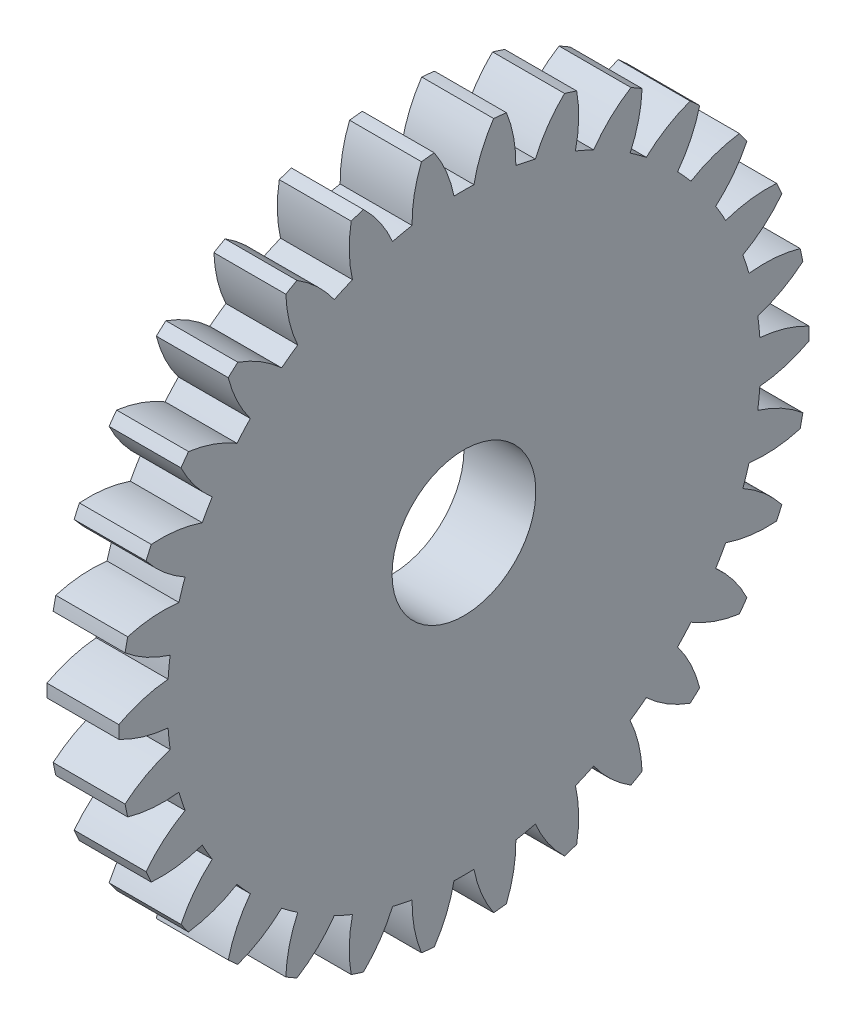
SolidWorks part; units mm, degrees
ref_plane "Plane1" through (0, 0, 0) normal (0, 0, 1) x (1, 0, 0)
ref_plane "Plane2" through (0, 0, 0) normal (0, 1, 0) x (1, 0, 0)
ref_plane "Plane3" through (0, 0, 0) normal (1, 0, 0) x (0, 0, -1)
sketch "HoldingSke" plane through (0, 0, 0) normal (0, 1, 0) x (1, 0, 0)
  line L0 (0, 0) -> (0.5774, -0.3333)
  line L1 (-15, 0) -> (100, 0) construction
  line L2 (0, 0) -> (-2.1039, 2.3779)
  line L3 (0, 0) -> (-11.863, 4.5341)
  line L4 (0, 0) -> (7.479, 4.318)
  line L5 (0, 0) -> (-46.8476, -17.4728)
  line L6 (0, 0) -> (-4.1448, -2.7965)
  line L7 (-2.1039, 2.3779) -> (8.6586, 51.2059)
  line L8 (-76.2, 54.61) -> (-74.4, 54.61)
  line L9 (-71.009, 38.7566) -> (-53.1078, 45.2721)
  line L10 (-76.2, 71.12) -> (104.1128, 71.12)
  line L11 (0, 0) -> (-5, 0)
  line L12 (-76.2, 101.6) -> (-76.147, 101.6)
  line L13 (24.9733, 27.94) -> (52.9518, 28.4284)
  line L14 (24.9733, 27.94) -> (24.9743, 27.94)
  line L15 (24.9733, 27.94) -> (100.4006, 29.5858)
  line L16 (-63.627, -1.5) -> (-12.827, -1.5)
  circle A0 centre (0, 0) radius 5
  circle A1 centre (0, 0) radius 20.624
  circle A2 centre (0, 0) radius 37.5
  circle A3 centre (0, 0) radius 5
  dimension "MHD" = 41.248
  dimension "Hub_dia" = 75
  dimension "Bore" = 10
  dimension "MBD" = 10
  dimension "Num_teeth" = 30
  dimension "Pitch" = 0.6667
  dimension "Overall_len" = 50
  dimension "Show_teeth" = 30
  dimension "OAL" = 50.0001
  dimension "T_dim" = 1.8
  dimension "Ap" = 20
  dimension "H" = 19.05
  dimension "Pitch_radius" = 180.3128
  dimension "Backlash" = 0.053
  dimension "Addendum_fac" = 1
  dimension "Dedendum_fac" = 1.25
  dimension "Clearance_fac" = 0.25
  dimension "Dedendum_add" = 0.001
  dimension "Module" = 1.5
sketch "BasProSke" plane through (0, 0, 0) normal (0, 1, 0) x (1, 0, 0)
  line L0 (-10, 0) -> (60, 0) construction
  line L1 (0, 0) -> (0, 24)
  line L2 (0, 0) -> (5, 0)
  line L3 (5, 0) -> (5, 24)
  line L4 (5, 24) -> (0, 24)
  dimension "Diameter" = 48
revolve "Base-Revolve" add sketch "BasProSke" angle 360 about L0
sketch "TooCutSke" plane through (0, 0, 0) normal (1, 0, 0) x (0, 0, -1)
  line L1 (0, 0) -> (0, 107) construction
  line L2 (0, 0) -> (-1.2703, 22.4641) construction
  line L3 (0, 0) -> (-4.6983, 44.7014) construction
  line L4 (-1.2703, 22.4641) -> (-2.3492, 22.3507) construction
  arc A0 (0.6933, 20.6123) -> (-0.6933, 20.6123) centre (0, 0) ccw
  arc A1 (2.0805, 23.9351) -> (-2.0805, 23.9351) centre (0, 0) ccw
  circle A2 centre (0, 0) radius 22.5 construction
  circle A3 centre (0, 0) radius 21.1431 construction
  arc A4 (-0.6933, 20.6123) -> (-2.0805, 23.9351) centre (-9.5243, 18.8764) ccw
  arc A5 (2.0805, 23.9351) -> (0.6933, 20.6123) centre (9.5243, 18.8764) ccw
  dimension "Root_dia" = 41.248
  dimension "Overcut_dia" = 48.0508
  dimension "Pitch_dia" = 45
  dimension "Base_dia" = 42.2862
  dimension "Flank_rad" = 9
  dimension "Half_ang" = 6
  dimension "Half_CT" = 1.0848
extrude "ToothCut" cut sketch "TooCutSke" along normal through all
fillet "Breaks" [suppressed] radius 0.03
fillet "RootFillets" [suppressed] radius 0.376
pattern_circular "TeethCuts" count 30 every 12 about axis through (-10, 0, 0) along (1, 0, 0) of "ToothCut", "RootFillets", "Breaks"
sketch "HubNeaOneSke" plane through (0, 0, 0) normal (-1, 0, 0) x (0, 0, 1)
  circle A0 centre (0, 0) radius 20.624
  dimension "Diameter" = 41.248
extrude "HubNearOne" [suppressed] add sketch "HubNeaOneSke" along normal blind 45.0001
sketch "HubNeaBotSke" plane through (0, 0, 0) normal (-1, 0, 0) x (0, 0, 1)
  circle A0 centre (0, 0) radius 20.624
  dimension "Diameter" = 41.248
extrude "HubNearBoth" [suppressed] add sketch "HubNeaBotSke" along normal blind 22.5
ref_plane "FarPln" through (5, 0, 0) normal (1, 0, 0) x (0, 0, -1)
sketch "HubFarSke" plane through (5, 0, 0) normal (1, 0, 0) x (0, 0, -1)
  circle A0 centre (0, 0) radius 20.624
  dimension "Diameter" = 41.248
extrude "HubFar" [suppressed] add sketch "HubFarSke" along normal blind 22.5
sketch "BorSke" plane through (0, 0, 0) normal (1, 0, 0) x (0, 0, -1)
  circle A0 centre (0, 0) radius 5
  dimension "Diameter" = 10
extrude "Bore" cut sketch "BorSke" along normal mid plane 100.0001
sketch "KeySke" plane through (0, 0, 0) normal (1, 0, 0) x (0, 0, -1)
  line L0 (-2, 0) -> (-2, 6.8)
  line L1 (-2, 6.8) -> (2, 6.8)
  line L2 (2, 6.8) -> (2, 0)
  line L3 (0, 0) -> (0, 34) construction
  line L4 (-2, 0) -> (2, 0)
  dimension "Offset" = 6.8
  dimension "Width" = 4
extrude "Keyway" [suppressed] cut sketch "KeySke" along normal mid plane 100.0001
pattern_circular "Keyway2" [suppressed] count 2 every 90 about axis through (-10, 0, 0) along (1, 0, 0)
equation "' \"Module@HoldingSke\" = 6.35"
equation "' \"Num_teeth@HoldingSke\" = 12"
equation "' \"Ap@HoldingSke\" =  20"
equation "' \"Ap@HoldingSke\" = 20"
equation "' \"Width@HoldingSke\" = 0.5 * 25.4"
equation "' \"Hub_dia@HoldingSke\"= 1 * 25.4"
equation "' \"Hub_dia@HoldingSke\" = 1 * 25.4"
equation "' \"Overall_len@HoldingSke\" = 1.0 * 25.4"
equation "' \"Bore@HoldingSke\" = 0.75 * 25.4"
equation "' \"T_dim@HoldingSke\" = 0.1 * 25.4"
equation "' \"Width@KeySke\" = 0.25 * 25.4"
equation "' \"Show_teeth@HoldingSke\" = 13"
equation "' \"Backlash@HoldingSke\" = 0.009 * 25.4"
equation "' \"Addendum_fac@HoldingSke\" = 1.0"
equation "' \"Dedendum_fac@HoldingSke\" = 1.25"
equation "' \"Dedendum_add@HoldingSke\" = 0.00005 * 25.4"
equation "' \"Clearance_fac@HoldingSke\" = 0.25"
equation "\"Pitch@HoldingSke\" = 1 / \"Module@HoldingSke\""
equation "\"Overcut_dia@TooCutSke\" = (\"Num_teeth@HoldingSke\" + 2 * \"Addendum_fac@HoldingSke\") / \"Pitch@HoldingSke\" + 0.002 * 25.4"
equation "\"Pitch_dia@TooCutSke\" = \"Num_teeth@HoldingSke\" / \"Pitch@HoldingSke\""
equation "\"Base_dia@TooCutSke\" = \"Num_teeth@HoldingSke\" / \"Pitch@HoldingSke\" * cos((\"Ap@HoldingSke\"  * 3.14159265 / 180))"
equation "\"Root_dia@TooCutSke\" = (\"Num_teeth@HoldingSke\" + 2) / \"Pitch@HoldingSke\" - 2 * (\"Addendum_fac@HoldingSke\" + \"Dedendum_fac@HoldingSke\") / \"Pitch@HoldingSke\" - \"Dedendum_add@HoldingSke\" * 2"
equation "\"Half_ang@TooCutSke\" = 180 / \"Num_teeth@HoldingSke\""
equation "\"Half_CT@TooCutSke\" = \"Num_teeth@HoldingSke\" / \"Pitch@HoldingSke\" * sin((3.14159265 / 2 / \"Num_teeth@HoldingSke\")) / 2 - 7 * \"Backlash@HoldingSke\" / 4"
equation "\"Flank_rad@TooCutSke\" = \"Num_teeth@HoldingSke\" / \"Pitch@HoldingSke\" / 5"
equation "\"Radius@RootFillets\" = \"Clearance_fac@HoldingSke\" / \"Pitch@HoldingSke\" + \"Dedendum_add@HoldingSke\""
equation "\"Break_rad@Breaks\" = 0.02 / \"Pitch@HoldingSke\""
equation "\"Thickness@HoldingSke\" = \"Width@HoldingSke\""
equation "\"OAL@HoldingSke\" = \"Thickness@HoldingSke\""
equation "\"MHD@HoldingSke\" = (\"Num_teeth@HoldingSke\" + 2) / \"Pitch@HoldingSke\" - 2 * (\"Addendum_fac@HoldingSke\" + \"Dedendum_fac@HoldingSke\")  / \"Pitch@HoldingSke\" - \"Dedendum_add@HoldingSke\" * 2"
equation "\"MBD@HoldingSke\" = (\"Num_teeth@HoldingSke\" + 2) / \"Pitch@HoldingSke\" - 2 * (\"Addendum_fac@HoldingSke\" + \"Dedendum_fac@HoldingSke\")  / \"Pitch@HoldingSke\" - \"Dedendum_add@HoldingSke\" * 2 - 0.002 * 25.4"
equation "\"MHD@HoldingSke\" = ((sgn( \"MHD@HoldingSke\" - \"Hub_dia@HoldingSke\" )-1)*( \"MHD@HoldingSke\" - \"Hub_dia@HoldingSke\" ))/-2+ \"Hub_dia@HoldingSke\""
equation "\"MBD@HoldingSke\" = ((sgn( \"MBD@HoldingSke\" - \"Bore@HoldingSke\" )-1)*( \"MBD@HoldingSke\" - \"Bore@HoldingSke\" ))/-2+ \"Bore@HoldingSke\""
equation "\"OAL@HoldingSke\" = ((sgn( \"OAL@HoldingSke\" - \"Overall_len@HoldingSke\" )+1)*( \"OAL@HoldingSke\" - \"Overall_len@HoldingSke\" ))/2 + \"Overall_len@HoldingSke\" + 0.000002 * 25.4"
equation "\"Num_teeth@TeethCuts\" = int( \"Show_teeth@HoldingSke\" ) + 1"
equation "\"Num_teeth@TeethCuts\" = ((sgn( \"Num_teeth@TeethCuts\" - \"Num_teeth@HoldingSke\" )-1)*( \"Num_teeth@TeethCuts\" - \"Num_teeth@HoldingSke\" ))/-2+ \"Num_teeth@HoldingSke\""
equation "\"Num_teeth@TeethCuts\" = ((sgn( \"Num_teeth@TeethCuts\" - 2.0)+1)*( \"Num_teeth@TeethCuts\" - 2.0))/2 +2.0"
equation "\"Angle@TeethCuts\" = 360.0 / \"Num_teeth@HoldingSke\""
equation "\"Diameter@BasProSke\" = (\"Num_teeth@HoldingSke\" + 2 * \"Addendum_fac@HoldingSke\") / \"Pitch@HoldingSke\""
equation "\"Thickness@BasProSke\"  = \"Thickness@HoldingSke\""
equation "' \"Fillet_rad@BasProSke\" =  \"Thickness@HoldingSke\" * 0.05"
equation "' \"Fillet_rad@BasProSke\" = \"Thickness@HoldingSke\" * 0.05"
equation "\"MHD@HoldingSke\" = ((sgn( \"MHD@HoldingSke\" - \"Root_dia@TooCutSke\" )-1)*( \"MHD@HoldingSke\" - \"Root_dia@TooCutSke\" ))/-2+ \"Root_dia@TooCutSke\""
equation "\"Diameter@HubNeaOneSke\" = \"MHD@HoldingSke\""
equation "\"Length@HubNearOne\" = \"OAL@HoldingSke\" - \"Thickness@BasProSke\""
equation "\"Diameter@HubNeaBotSke\" = \"MHD@HoldingSke\""
equation "\"Length@HubNearBoth\" = ( \"OAL@HoldingSke\" - \"Thickness@BasProSke\" ) / 2.0"
equation "\"Thickness@FarPln\" = \"Thickness@BasProSke\""
equation "\"Diameter@HubFarSke\" = \"MHD@HoldingSke\""
equation "\"Length@HubFar\" = ( \"OAL@HoldingSke\" - \"Thickness@BasProSke\" ) / 2.0"
equation "\"Diameter@BorSke\" = \"MBD@HoldingSke\""
equation "\"D1@Bore\" = \"OAL@HoldingSke\" * 2.0"
equation "\"D1@Keyway\" = \"OAL@HoldingSke\" * 2.0"
equation "\"Offset@KeySke\" = \"T_dim@HoldingSke\" + \"MBD@HoldingSke\" / 2.0"
